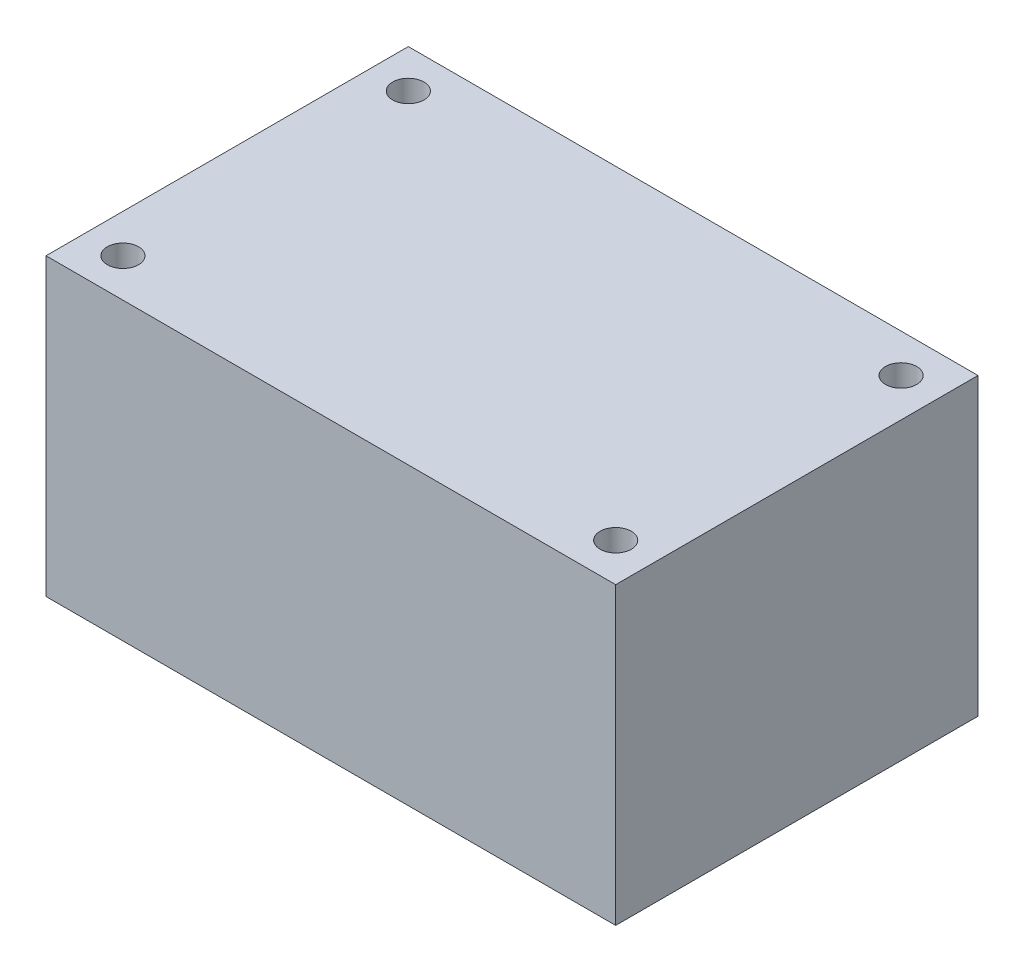
SolidWorks part; units mm, degrees
ref_plane "Front Plane" through (0, 0, 0) normal (0, 0, 1) x (1, 0, 0)
ref_plane "Top Plane" through (0, 0, 0) normal (0, 1, 0) x (1, 0, 0)
ref_plane "Right Plane" through (0, 0, 0) normal (1, 0, 0) x (0, 0, -1)
sketch "Sketch1" plane through (0, 0, 0) normal (0, 1, 0) x (1, 0, 0)
  line L1 (-28.955, 18.415) -> (28.955, 18.415)
  line L2 (-28.955, 18.415) -> (-28.955, -18.415)
  line L3 (-28.955, -18.415) -> (28.955, -18.415)
  line L4 (28.955, 18.415) -> (28.955, -18.415)
  line L5 (-28.955, 18.415) -> (28.955, -18.415) construction
  line L6 (-28.955, -18.415) -> (28.955, 18.415) construction
  line L7 (-25.045, 14.505) -> (25.045, 14.505) construction
  line L8 (-25.045, 14.505) -> (-25.045, -14.505) construction
  line L9 (-25.045, -14.505) -> (25.045, -14.505) construction
  line L10 (25.045, 14.505) -> (25.045, -14.505) construction
  line L11 (-25.045, 14.505) -> (25.045, -14.505) construction
  line L12 (-25.045, -14.505) -> (25.045, 14.505) construction
  circle A0 centre (-25.045, 14.505) radius 1.5875
  circle A1 centre (25.045, 14.505) radius 1.5875
  circle A2 centre (25.045, -14.505) radius 1.5875
  circle A3 centre (-25.045, -14.505) radius 1.5875
  point P0 (0, 0)
  point P6 (0, 0)
  dimension "D1" = 3.175
  dimension "D2" = 54
  dimension "D3" = 3.91
  dimension "D4" = 3.91
  dimension "D5" = 32.92
extrude "Boss-Extrude1" add sketch "Sketch1" along normal blind 30
